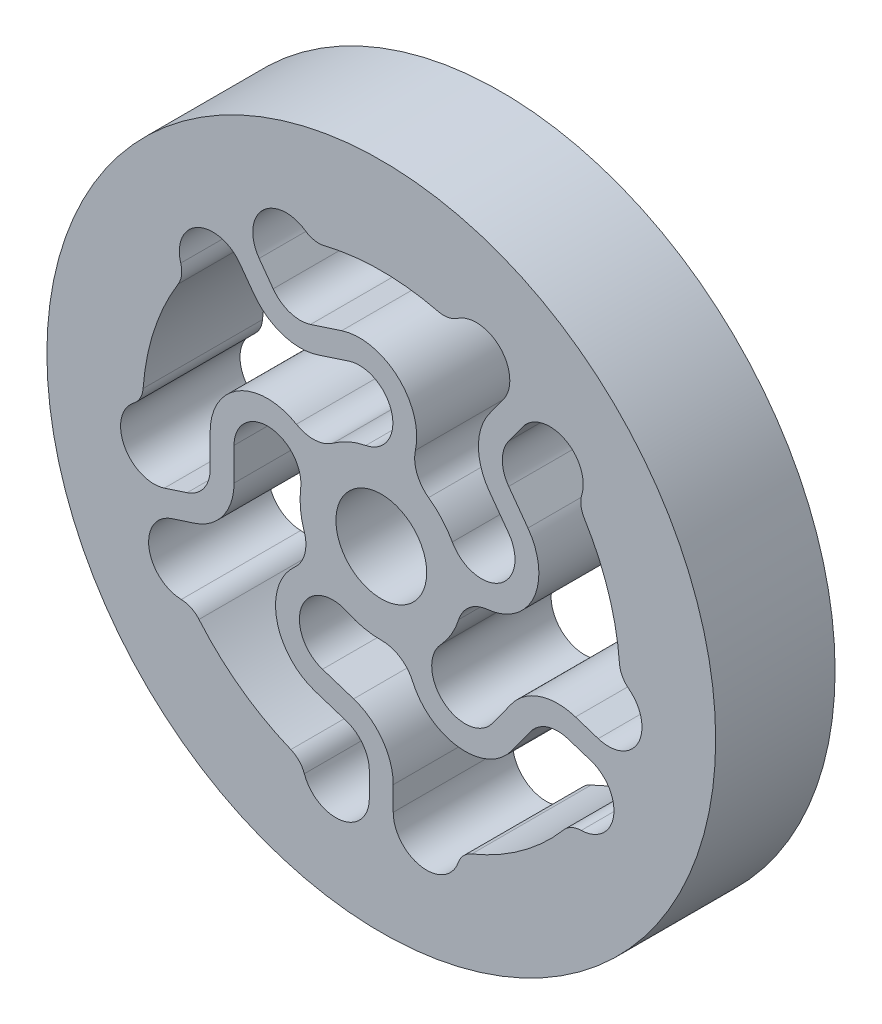
SolidWorks part; units mm, degrees
ref_plane "Front Plane" through (0, 0, 0) normal (0, 0, 1) x (1, 0, 0)
ref_plane "Top Plane" through (0, 0, 0) normal (0, 1, 0) x (1, 0, 0)
ref_plane "Right Plane" through (0, 0, 0) normal (1, 0, 0) x (0, 0, -1)
sketch "Sketch1" plane through (0, 0, 0) normal (0, 0, 1) x (1, 0, 0)
  circle A0 centre (0, 0) radius 14
  circle A1 centre (0, 0) radius 10
  circle A2 centre (0, 0) radius 1.9
  circle A3 centre (0, 0) radius 3.4
  dimension "D1" = 28
  dimension "D2" = 4
  dimension "D3" = 3.8
  dimension "D4" = 1.5
extrude "Boss-Extrude1" add sketch "Sketch1" along normal blind 5 contours A3 A2 | A0 A1
sketch "Sketch3" plane through (0, 0, 5) normal (0, 0, 1) x (1, 0, 0)
  line L0 (0, 0) -> (-2.0286, -4.3503) construction
  line L1 (0, 0) -> (0, -14) construction
  line L2 (-1.9, -8.3875) -> (1.9, -8.3875) construction
  line L3 (-2.4611, -5.6818) -> (-1.1585, -6.1049)
  line L4 (-2.77, -6.6329) -> (-1.4675, -7.056)
  line L5 (-6.1642, 0.5849) -> (-6.1641, -0.7847)
  line L6 (-7.1642, 0.5848) -> (-7.1641, -0.7848)
  line L7 (-1.3486, 6.0433) -> (-2.6511, 5.6199)
  line L8 (-1.6577, 6.9943) -> (-2.9602, 6.571)
  line L9 (5.3307, 3.1501) -> (4.5256, 4.258)
  line L10 (6.1397, 3.7379) -> (5.3346, 4.8458)
  line L11 (4.6432, -4.0964) -> (5.4481, -2.9884)
  line L12 (5.4523, -4.6841) -> (6.2572, -3.5761)
  line L13 (-4.1354, -3.2009) -> (-6.4572, -1.9343) construction
  arc A0 (-1.4369, -3.0814) -> (-2.4611, -5.6818) centre (-2.0286, -4.3503) ccw
  arc A1 (-3.6246, -2.5578) -> (-2.77, -6.6329) centre (-2.0286, -4.3503) ccw
  arc A2 (-3.2269, -1.0712) -> (-1.4369, -3.0814) centre (0, 0) ccw
  arc A3 (-3.6246, -2.5578) -> (-3.2269, -1.0712) centre (-4.5556, -1.5123) ccw
  arc A4 (-2.2093, -9.7529) -> (-1.4675, -7.056) centre (-1.9, -8.3875) ccw
  arc A5 (0.5, -8.3875) -> (-1.1585, -6.1049) centre (-1.9, -8.3875) ccw
  arc A6 (0.5, -8.3875) -> (2.2093, -9.7529) centre (1.9, -8.3875) ccw
  arc A7 (-2.2093, -9.7529) -> (2.2093, -9.7529) centre (0, 0) ccw
  circle A8 centre (0, 0) radius 10 construction
  circle A9 centre (0, 0) radius 3.4 construction
  circle A10 centre (0, 0) radius 14 construction
  arc A11 (-3.3747, 0.4144) -> (-6.1642, 0.5849) centre (-4.7642, 0.585) ccw
  arc A12 (-3.5527, 2.6567) -> (-7.1642, 0.5848) centre (-4.7642, 0.585) ccw
  arc A13 (-2.0159, 2.7379) -> (-3.3747, 0.4144) centre (0, 0) ccw
  arc A14 (-3.5527, 2.6567) -> (-2.0159, 2.7379) centre (-2.846, 3.8653) ccw
  arc A15 (-9.9583, -0.9126) -> (-7.1641, -0.7848) centre (-8.5641, -0.7849) ccw
  arc A16 (-7.8225, -3.0674) -> (-6.1641, -0.7847) centre (-8.5641, -0.7849) ccw
  arc A17 (-7.8225, -3.0674) -> (-8.5928, -5.115) centre (-7.3898, -4.3989) ccw
  arc A18 (-9.9583, -0.9126) -> (-8.5928, -5.115) centre (0, 0) ccw
  arc A19 (-0.6488, 3.3375) -> (-1.3486, 6.0433) centre (-0.9159, 4.7118) ccw
  arc A20 (1.4289, 4.1998) -> (-1.6577, 6.9943) centre (-0.9159, 4.7118) ccw
  arc A21 (1.981, 2.7633) -> (-0.6488, 3.3375) centre (0, 0) ccw
  arc A22 (1.4289, 4.1998) -> (1.981, 2.7633) centre (2.7966, 3.9011) ccw
  arc A23 (-3.9452, 9.1889) -> (-2.9602, 6.571) centre (-3.3929, 7.9024) ccw
  arc A24 (-5.3346, 6.4917) -> (-2.6511, 5.6199) centre (-3.3929, 7.9024) ccw
  arc A25 (-5.3346, 6.4917) -> (-7.52, 6.5917) centre (-6.4672, 5.6688) ccw
  arc A26 (-3.9452, 9.1889) -> (-7.52, 6.5917) centre (0, 0) ccw
  arc A27 (2.9737, 1.6484) -> (5.3307, 3.1501) centre (4.1982, 2.3271) ccw
  arc A28 (4.4358, -0.0611) -> (6.1397, 3.7379) centre (4.1982, 2.3271) ccw
  arc A29 (3.2402, -1.0301) -> (2.9737, 1.6484) centre (0, 0) ccw
  arc A30 (4.4358, -0.0611) -> (3.2402, -1.0301) centre (4.5744, -1.4542) ccw
  arc A31 (7.52, 6.5917) -> (5.3346, 4.8458) centre (6.4672, 5.6688) ccw
  arc A32 (4.5255, 7.0795) -> (4.5256, 4.258) centre (6.4672, 5.6688) ccw
  arc A33 (4.5255, 7.0795) -> (3.9452, 9.1889) centre (3.3929, 7.9024) ccw
  arc A34 (7.52, 6.5917) -> (3.9452, 9.1889) centre (0, 0) ccw
  arc A35 (2.4866, -2.3188) -> (4.6432, -4.0964) centre (3.5105, -3.2736) ccw
  arc A36 (1.3126, -4.2376) -> (5.4523, -4.6841) centre (3.5105, -3.2736) ccw
  arc A37 (0.0216, -3.3999) -> (2.4866, -2.3188) centre (0, 0) ccw
  arc A38 (1.3126, -4.2376) -> (0.0216, -3.3999) centre (0.0305, -4.7999) ccw
  arc A39 (8.5928, -5.115) -> (6.2572, -3.5761) centre (7.3898, -4.3989) ccw
  arc A40 (8.1315, -2.1163) -> (5.4481, -2.9884) centre (7.3898, -4.3989) ccw
  arc A41 (8.1315, -2.1163) -> (9.9583, -0.9126) centre (8.5641, -0.7849) ccw
  arc A42 (8.5928, -5.115) -> (9.9583, -0.9126) centre (0, 0) ccw
  point P39 (0, 0)
  point P54 (0, 0)
  point P69 (0, 0)
  point P71 (0, 0)
  point P85 (0, 0)
  point P86 (0, 0)
  dimension "D1" = 1.4
  dimension "D2" = 1
  dimension "D3" = 25
  dimension "D5" = 2.6448
  dimension "D4" = 5
extrude "Boss-Extrude3" add sketch "Sketch3" against normal up to surface (5 mm away) up to face at (10, 0, 0)
sketch "Sketch4" plane through (0, 0, 5) normal (0, 0, 1) x (1, 0, 0)
  line L0 (0.5, -8.3875) -> (0.5, -9.3875)
  line L1 (0, 0) -> (0, -20.2141) construction
  line L2 (-0.5, -8.3875) -> (-0.5, -9.3875)
  line L3 (-7.8225, -3.0674) -> (-8.7735, -3.3764)
  line L4 (-8.1315, -2.1163) -> (-9.0825, -2.4254)
  line L5 (-5.3346, 6.4917) -> (-5.9223, 7.3007)
  line L6 (-4.5255, 7.0795) -> (-5.1133, 7.8885)
  line L7 (4.5255, 7.0795) -> (5.1133, 7.8885)
  line L8 (5.3346, 6.4917) -> (5.9223, 7.3007)
  line L9 (8.1315, -2.1163) -> (9.0825, -2.4254)
  line L10 (7.8225, -3.0674) -> (8.7735, -3.3764)
  arc A0 (0.5, -9.3875) -> (3.2213, -9.8504) centre (1.9, -9.3875) ccw
  arc A1 (0.5, -8.3875) -> (2.2093, -9.7529) centre (1.9, -8.3875) ccw construction
  arc A3 (2.2093, -9.7529) -> (8.5928, -5.115) centre (0, 0) ccw construction
  arc A4 (3.7864, -9.2554) -> (3.2213, -9.8504) centre (4.165, -10.181) ccw
  arc A5 (0.5, -8.3875) -> (2.2093, -9.7529) centre (1.9, -8.3875) ccw
  arc A6 (2.2093, -9.7529) -> (3.7864, -9.2554) centre (0, 0) ccw
  arc A7 (-2.2093, -9.7529) -> (-3.7864, -9.2554) centre (0, 0) cw
  arc A8 (-0.5, -8.3875) -> (-2.2093, -9.7529) centre (-1.9, -8.3875) cw
  arc A9 (-3.7864, -9.2554) -> (-3.2213, -9.8504) centre (-4.165, -10.181) cw
  arc A10 (-0.5, -9.3875) -> (-3.2213, -9.8504) centre (-1.9, -9.3875) cw
  arc A11 (-8.7735, -3.3764) -> (-8.3728, -6.1075) centre (-8.3409, -4.7079) ccw
  arc A12 (-7.6324, -6.4612) -> (-8.3728, -6.1075) centre (-8.3956, -7.1073) ccw
  arc A13 (-7.8225, -3.0674) -> (-8.5928, -5.115) centre (-7.3898, -4.3989) ccw
  arc A14 (-8.5928, -5.115) -> (-7.6324, -6.4612) centre (0, 0) ccw
  arc A15 (-9.9583, -0.9126) -> (-9.9725, 0.741) centre (0, 0) cw
  arc A16 (-8.1315, -2.1163) -> (-9.9583, -0.9126) centre (-8.5641, -0.7849) cw
  arc A17 (-9.9725, 0.741) -> (-10.3637, 0.0197) centre (-10.9698, 0.8151) cw
  arc A18 (-9.0825, -2.4254) -> (-10.3637, 0.0197) centre (-9.5152, -1.0939) cw
  arc A19 (-5.9223, 7.3007) -> (-8.396, 6.0757) centre (-7.055, 6.4778) ccw
  arc A20 (-8.5035, 5.2622) -> (-8.396, 6.0757) centre (-9.3538, 5.7884) ccw
  arc A21 (-5.3346, 6.4917) -> (-7.52, 6.5917) centre (-6.4672, 5.6688) ccw
  arc A22 (-7.52, 6.5917) -> (-8.5035, 5.2622) centre (0, 0) ccw
  arc A23 (-3.9452, 9.1889) -> (-2.377, 9.7134) centre (0, 0) cw
  arc A24 (-4.5255, 7.0795) -> (-3.9452, 9.1889) centre (-3.3929, 7.9024) cw
  arc A25 (-2.377, 9.7134) -> (-3.1838, 9.8625) centre (-2.6147, 10.6847) cw
  arc A26 (-5.1133, 7.8885) -> (-3.1838, 9.8625) centre (-3.9807, 8.7114) cw
  arc A27 (5.1133, 7.8885) -> (3.1838, 9.8625) centre (3.9807, 8.7114) ccw
  arc A28 (2.377, 9.7134) -> (3.1838, 9.8625) centre (2.6147, 10.6847) ccw
  arc A29 (4.5255, 7.0795) -> (3.9452, 9.1889) centre (3.3929, 7.9024) ccw
  arc A30 (3.9452, 9.1889) -> (2.377, 9.7134) centre (0, 0) ccw
  arc A31 (7.52, 6.5917) -> (8.5035, 5.2622) centre (0, 0) cw
  arc A32 (5.3346, 6.4917) -> (7.52, 6.5917) centre (6.4672, 5.6688) cw
  arc A33 (8.5035, 5.2622) -> (8.396, 6.0757) centre (9.3538, 5.7884) cw
  arc A34 (5.9223, 7.3007) -> (8.396, 6.0757) centre (7.055, 6.4778) cw
  arc A35 (9.0825, -2.4254) -> (10.3637, 0.0197) centre (9.5152, -1.0939) ccw
  arc A36 (9.9725, 0.741) -> (10.3637, 0.0197) centre (10.9698, 0.8151) ccw
  arc A37 (8.1315, -2.1163) -> (9.9583, -0.9126) centre (8.5641, -0.7849) ccw
  arc A38 (9.9583, -0.9126) -> (9.9725, 0.741) centre (0, 0) ccw
  arc A39 (8.5928, -5.115) -> (7.6324, -6.4612) centre (0, 0) cw
  arc A40 (7.8225, -3.0674) -> (8.5928, -5.115) centre (7.3898, -4.3989) cw
  arc A41 (7.6324, -6.4612) -> (8.3728, -6.1075) centre (8.3956, -7.1073) cw
  arc A42 (8.7735, -3.3764) -> (8.3728, -6.1075) centre (8.3409, -4.7079) cw
  point P85 (0, 0)
  dimension "D1" = 1
  dimension "D2" = 1
  dimension "D3" = 5
extrude "Cut-Extrude1" cut sketch "Sketch4" against normal through all
